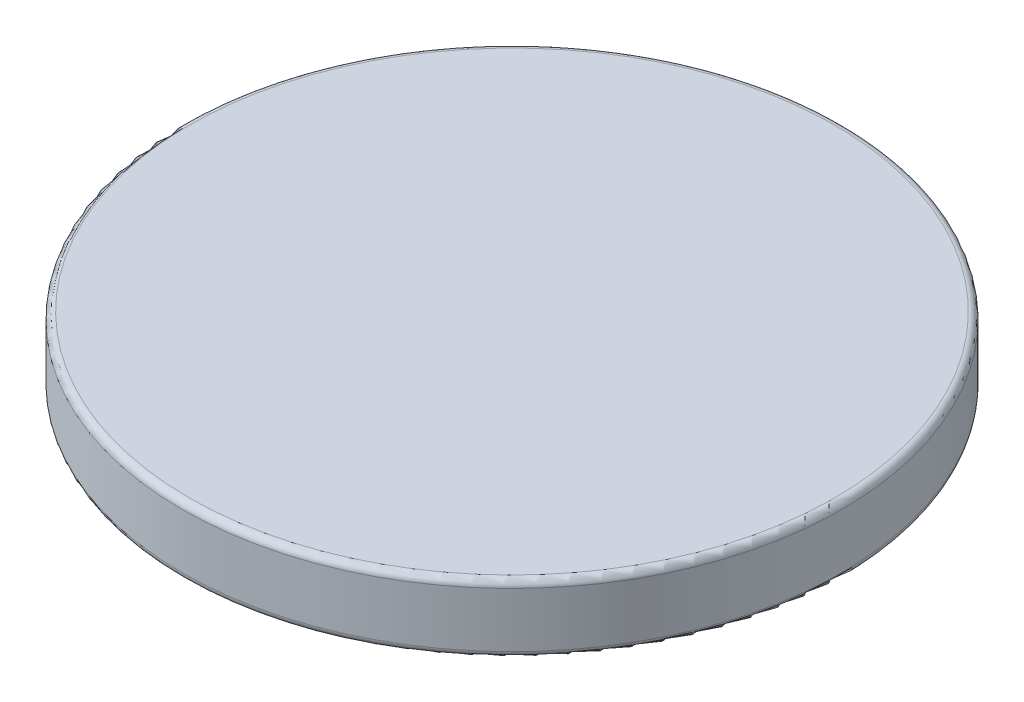
SolidWorks part; units mm, degrees
ref_plane "Front" through (0, 0, 0) normal (0, 0, 1) x (1, 0, 0)
ref_plane "Top" through (0, 0, 0) normal (0, 1, 0) x (1, 0, 0)
ref_plane "Right" through (0, 0, 0) normal (1, 0, 0) x (0, 0, -1)
sketch "Sketch2" plane through (0, 0, 0) normal (0, 1, 0) x (1, 0, 0)
  circle A0 centre (0, 0) radius 61.214
  dimension "D1" = 122.428
extrude "Boss-Extrude1" add sketch "Sketch2" against normal blind 12.7
fillet "Fillet1" radius 1.27 2 edges at (0, -12.7, 61.214) (0, 0, 61.214)
